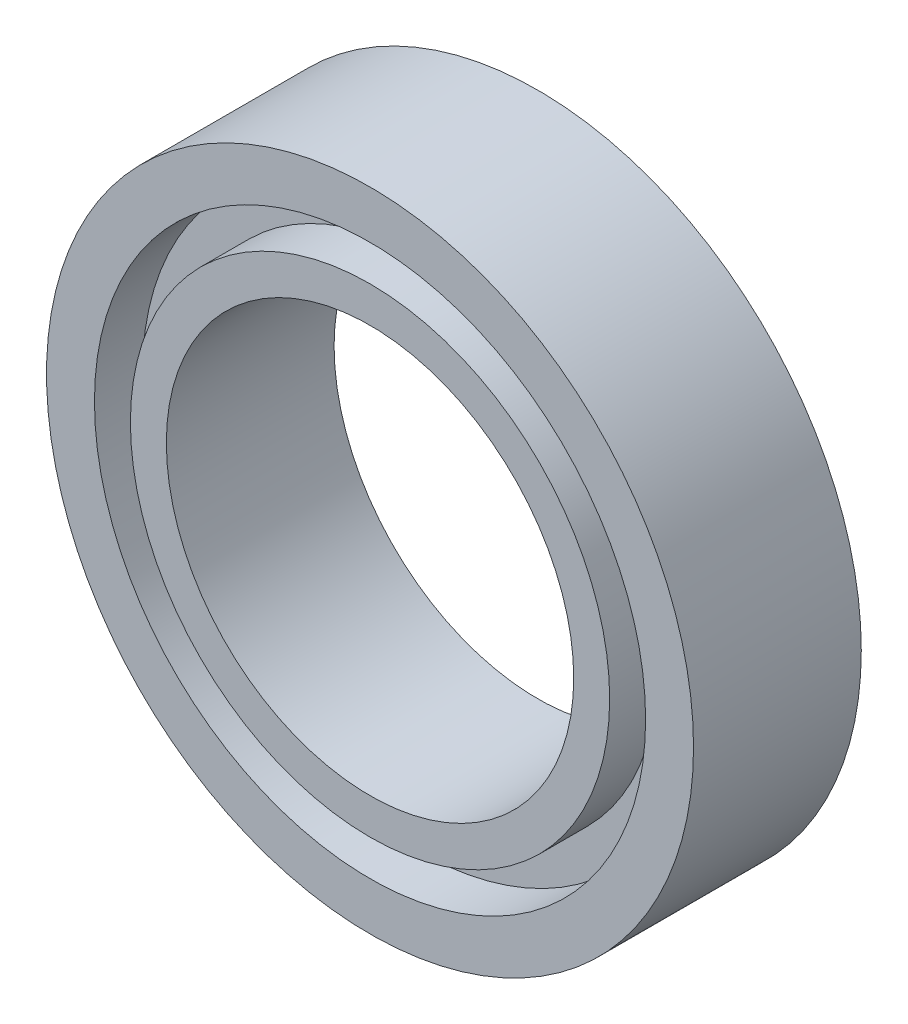
SolidWorks part; units mm, degrees
ref_plane "Front Plane" through (0, 0, 0) normal (0, 0, 1) x (1, 0, 0)
ref_plane "Top Plane" through (0, 0, 0) normal (0, 1, 0) x (1, 0, 0)
ref_plane "Right Plane" through (0, 0, 0) normal (1, 0, 0) x (0, 0, -1)
sketch "Sketch1" plane through (0, 0, 0) normal (0, 0, 1) x (1, 0, 0)
  circle A0 centre (0, 0) radius 13.5
  circle A1 centre (0, 0) radius 8.5
  dimension "D1" = 27
  dimension "D2" = 17
extrude "Boss-Extrude1" add sketch "Sketch1" along normal blind 7
sketch "Sketch2" plane through (0, 0, 7) normal (0, 0, 1) x (1, 0, 0)
  circle A1 centre (0, 0) radius 10
  circle A2 centre (0, 0) radius 11.5
  circle A3 centre (0, 0) radius 11.5
  dimension "D1" = 2
  dimension "D2" = 1.5
extrude "Cut-Extrude1" cut sketch "Sketch2" against normal blind 2 contours A3 | A1
